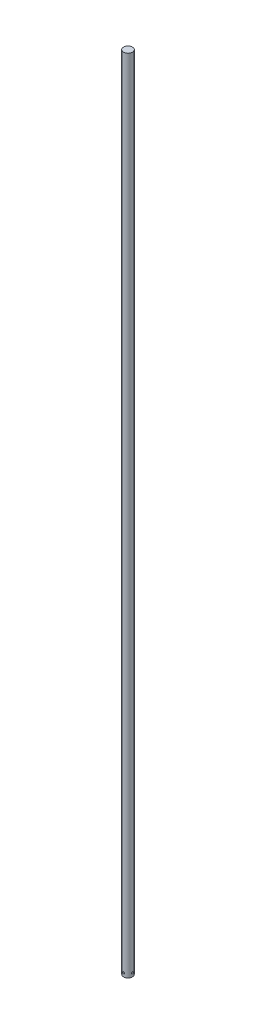
SolidWorks part; units mm, degrees
ref_plane "Front Plane" through (0, 0, 0) normal (0, 0, 1) x (1, 0, 0)
ref_plane "Top Plane" through (0, 0, 0) normal (0, 1, 0) x (1, 0, 0)
ref_plane "Right Plane" through (0, 0, 0) normal (1, 0, 0) x (0, 0, -1)
sketch "Sketch1" plane through (0, 0, 0) normal (0, 1, 0) x (1, 0, 0)
  circle A0 centre (0, 0) radius 5
  dimension "D1" = 10
extrude "Boss-Extrude1" add sketch "Sketch1" along normal blind 900
sketch "Sketch2" plane through (0, 0, 0) normal (1, 0, 0) x (0, 0, -1)
  line L0 (-5, 0) -> (5, 0) construction
  line L1 (-5, 0) -> (5, 0) construction
  circle A0 centre (0, 4) radius 1
  point P4 (0, 0)
  dimension "D1" = 2
  dimension "D2" = 4
extrude "Cut-Extrude1" cut sketch "Sketch2" against normal blind 900
pattern_circular "CirPattern1" count 4 over 360 about axis through (0, 0, 0) along (0, 1, 0) of "Cut-Extrude1"
